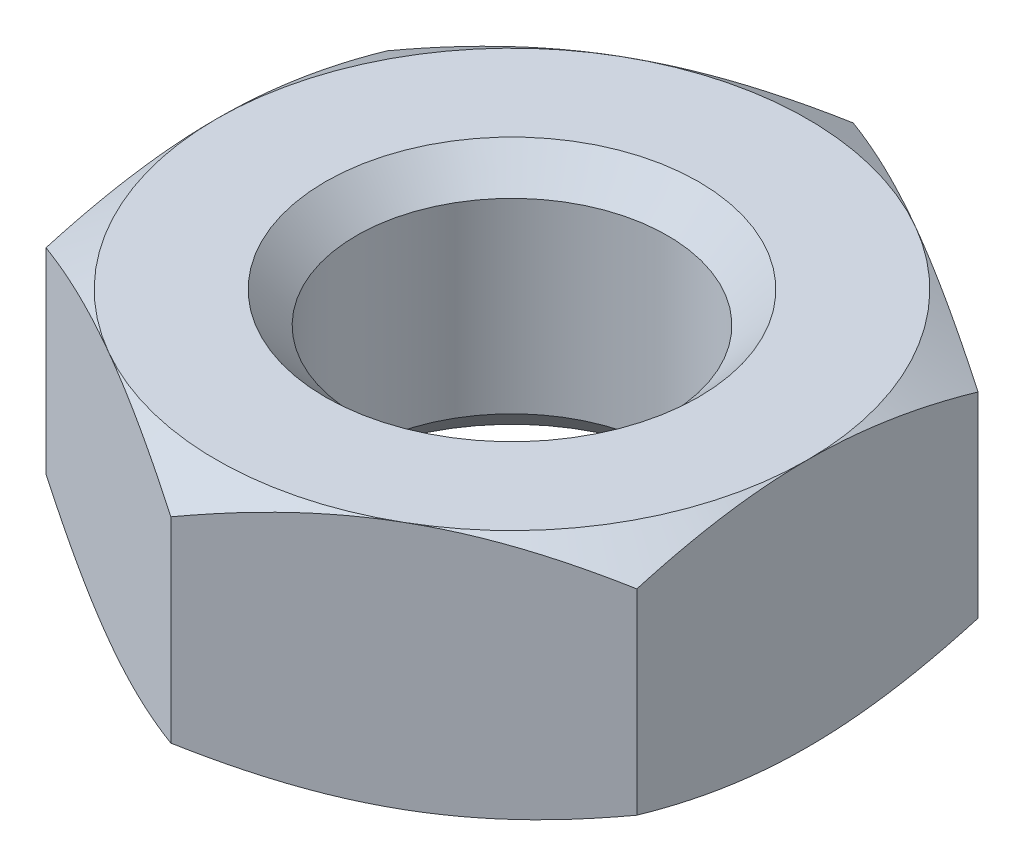
SolidWorks part; units mm, degrees
ref_plane "Front Plane" through (0, 0, 0) normal (0, 0, 1) x (1, 0, 0)
ref_plane "Top Plane" through (0, 0, 0) normal (0, 1, 0) x (1, 0, 0)
ref_plane "Right Plane" through (0, 0, 0) normal (1, 0, 0) x (0, 0, -1)
sketch "Sketch1" plane through (0, 0, 0) normal (0, 1, 0) x (1, 0, 0)
  line L1 (9.5, -5.4848) -> (9.5, 5.4848)
  line L2 (9.5, 5.4848) -> (0, 10.9697)
  line L3 (0, 10.9697) -> (-9.5, 5.4848)
  line L4 (-9.5, 5.4848) -> (-9.5, -5.4848)
  line L5 (-9.5, -5.4848) -> (0, -10.9697)
  line L6 (0, -10.9697) -> (9.5, -5.4848)
  circle A0 centre (0, 0) radius 9.5 construction
  circle A1 centre (0, 0) radius 5
  dimension "D2" = 10
  dimension "D1" = 19
extrude "Boss-Extrude1" add sketch "Sketch1" along normal blind 8
chamfer "Chamfer1" distance 1 angle 45 2 edges at (0, 0, 5) (0, 8, 5)
sketch "Sketch2" plane through (0, 8, 0) normal (0, 1, 0) x (1, 0, 0)
  circle A0 centre (0, 0) radius 9.5
extrude "Cut-Extrude1" cut sketch "Sketch2" against normal blind 8 draft 60 flip side to cut
sketch "Sketch3" plane through (0, 0, 0) normal (0, -1, 0) x (1, 0, 0)
  circle A0 centre (0, 0) radius 9.5
extrude "Cut-Extrude2" cut sketch "Sketch3" against normal blind 8 draft 60 flip side to cut
